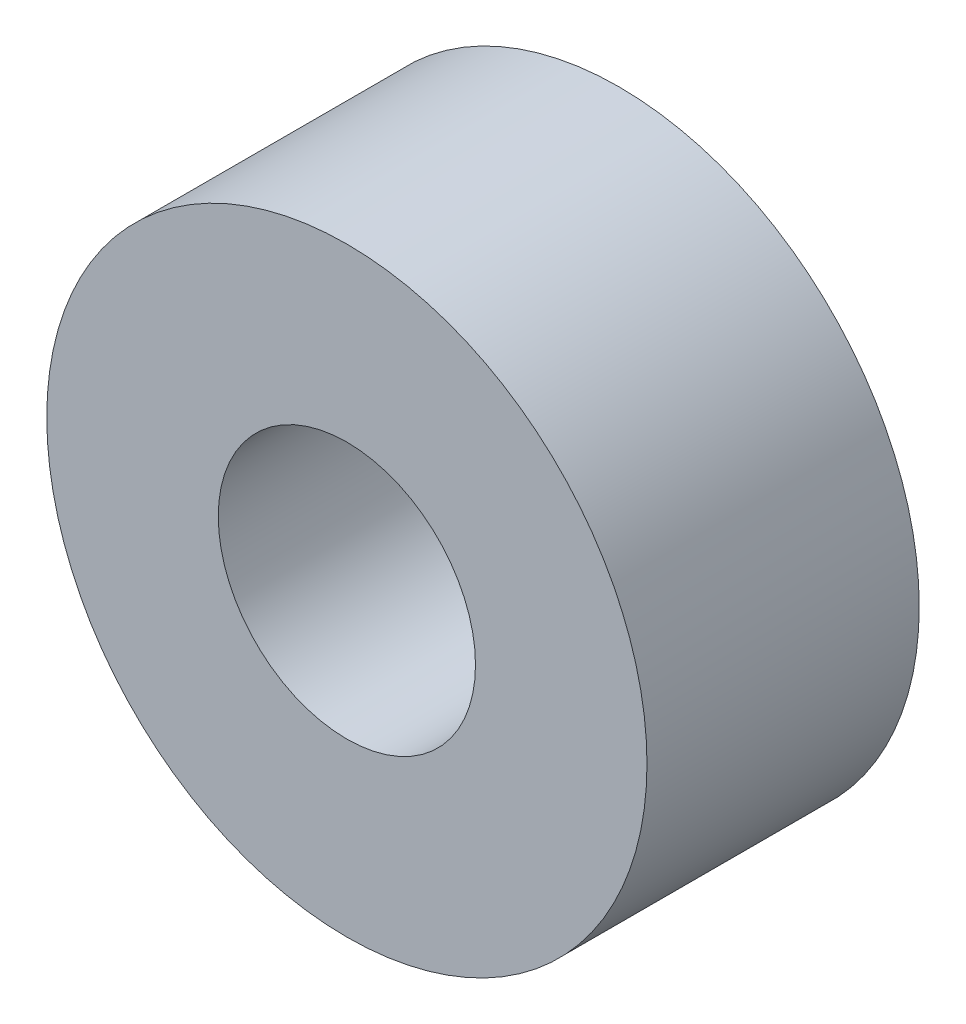
SolidWorks part; units mm, degrees
ref_plane "Front Plane" through (0, 0, 0) normal (0, 0, 1) x (1, 0, 0)
ref_plane "Top Plane" through (0, 0, 0) normal (0, 1, 0) x (1, 0, 0)
ref_plane "Right Plane" through (0, 0, 0) normal (1, 0, 0) x (0, 0, -1)
sketch "Sketch1" plane through (0, 0, 0) normal (0, 0, 1) x (1, 0, 0)
  circle A0 centre (0, 0) radius 1.5
  circle A1 centre (0, 0) radius 3.5
  dimension "D1" = 3
  dimension "D2" = 7
extrude "Boss-Extrude1" add sketch "Sketch1" along normal blind 3.175
